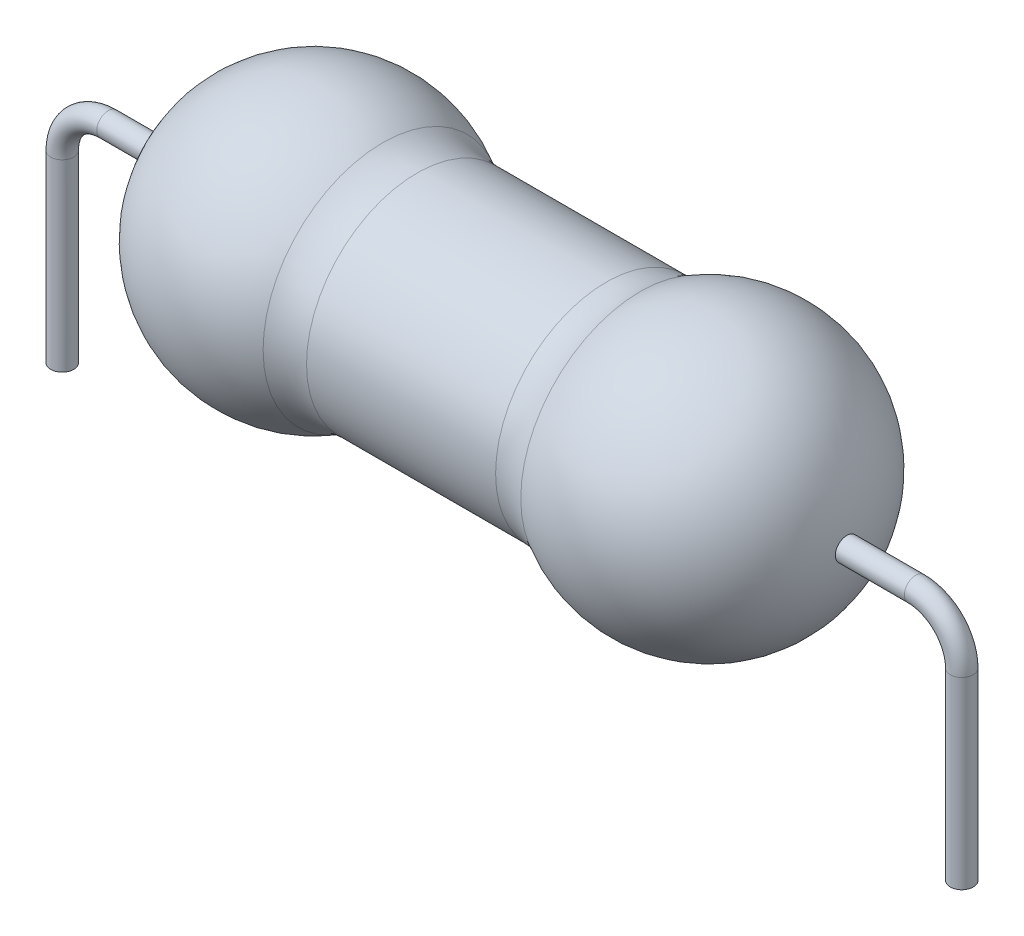
SolidWorks part; units mm, degrees
ref_plane "Ön Düzlem" through (0, 0, 0) normal (0, 0, 1) x (1, 0, 0)
ref_plane "Üst Düzlem" through (0, 0, 0) normal (0, 1, 0) x (1, 0, 0)
ref_plane "Sağ Düzlem" through (0, 0, 0) normal (1, 0, 0) x (0, 0, -1)
sketch "Çizim3" plane through (0, 0, 0) normal (0, 0, 1) x (1, 0, 0)
  line L0 (-17.9379, 4.8083) -> (-9.7112, 4.8083)
  line L1 (-5.2357, 0) -> (-22.4134, 0) construction
  line L3 (-40.9506, 0) -> (16.6709, 0) construction
  line L4 (-28.4134, 0) -> (0.7643, 0)
  arc A0 (-19.4298, 5.2056) -> (-28.4134, 0) centre (-22.4134, 0) ccw
  arc A1 (0.7643, 0) -> (-8.2193, 5.2056) centre (-5.2357, 0) ccw
  arc A2 (-17.9379, 4.8083) -> (-19.4298, 5.2056) centre (-17.9379, 7.8083) cw
  arc A3 (-8.2193, 5.2056) -> (-9.7112, 4.8083) centre (-9.7112, 7.8083) cw
  point P11 (-18.8246, 4.8083)
  point P14 (-8.8246, 4.8083)
  dimension "D1" = 12
  dimension "D2" = 12
  dimension "D4" = 3
  dimension "D5" = 3
  dimension "D3" = 10
  dimension "D6" = 29.1777
revolve "Döndür2" add sketch "Çizim3" angle 360 about L4
ref_plane "Düzlem1" through (-19.4298, 0, 0) normal (1, 0, 0) x (0, 0, -1)
ref_plane "Düzlem4" through (-28.4134, 0, 0) normal (1, 0, 0) x (0, 0, -1)
sketch3d "3B Çizim4"
  line L0 (-33.4156, -2.1034, -0.0417) -> (-33.4156, -10.1034, -0.0417)
  line L1 (-28.4156, -0.1034, -0.0417) -> (-31.4156, -0.1034, -0.0417)
  arc A0 (-33.4156, -2.1034, -0.0417) -> (-31.4156, -0.1034, -0.0417) centre (-31.4156, -2.1034, -0.0417) ccw
  point P5 (-33.4156, -0.1034, -0.0417)
  point P6 (-31.4156, -2.1034, -2.0417)
  dimension "D3" = 2
  dimension "D1" = 5
  dimension "D2" = 10
ref_plane "Düzlem5" through (-33.4156, -10.1034, -0.0417) normal (0, -1, 0) x (-1, 0, 0)
sketch "Çizim6" plane through (-33.4156, -10.1034, -0.0417) normal (0, -1, 0) x (-1, 0, 0)
  circle A0 centre (0, 0) radius 0.5
  dimension "D1" = 1
sweep "Süpür2" add profiles "Çizim6" path "3B Çizim4"
ref_plane "Düzlem6" through (0.7643, 0, 0) normal (1, 0, 0) x (0, 0, -1)
sketch3d "3B Çizim6"
  line L0 (0.7631, 0.0028, 0) -> (3.7631, 0.0028, 0)
  line L1 (5.7631, -1.9972, 0) -> (5.7631, -9.9972, 0)
  arc A0 (3.7631, 0.0028, 0) -> (5.7631, -1.9972, 0) centre (3.7631, -1.9972, 0) ccw
  point P5 (5.7631, 0.0028, 0)
  point P6 (3.7631, -1.9972, -2)
  dimension "D3" = 2
  dimension "D1" = 5
  dimension "D2" = 10
ref_plane "Düzlem8" through (5.7631, -9.9972, 0) normal (0, -1, 0) x (-1, 0, 0)
sketch "Çizim12" plane through (5.7631, -9.9972, 0) normal (0, -1, 0) x (-1, 0, 0)
  circle A0 centre (0, 0) radius 0.5
  dimension "D1" = 1
sweep "Süpür4" add profiles "Çizim12" path "3B Çizim6"
